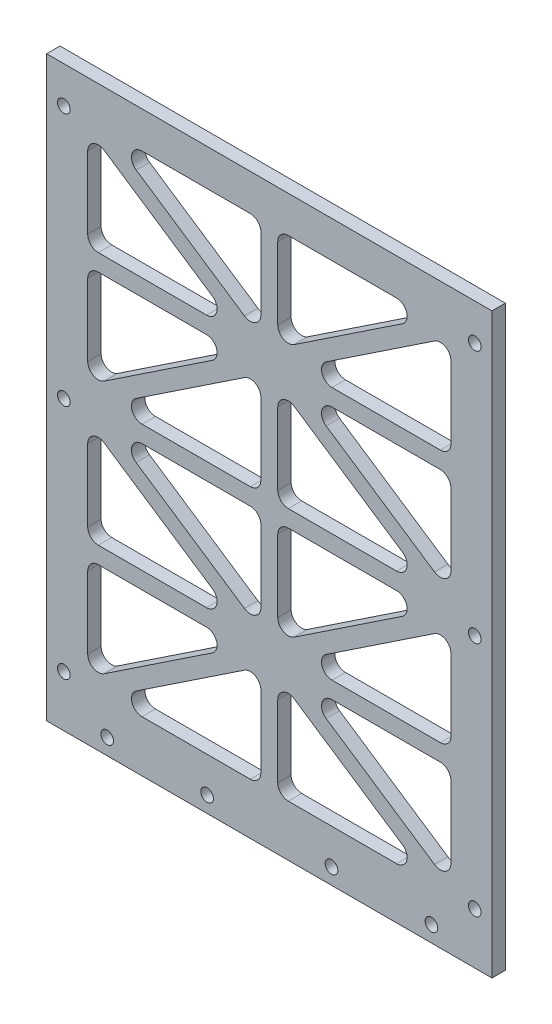
SolidWorks part; units mm, degrees
ref_plane "Front Plane" through (0, 0, 0) normal (0, 0, 1) x (1, 0, 0)
ref_plane "Top Plane" through (0, 0, 0) normal (0, 1, 0) x (1, 0, 0)
ref_plane "Right Plane" through (0, 0, 0) normal (1, 0, 0) x (0, 0, -1)
sketch "Sketch1" plane through (0, 0, 0) normal (0, 0, 1) x (1, 0, 0)
  line L0 (0, -116.2131) -> (0, -56.2131) construction
  line L1 (4, 119.7869) -> (4, 71.261)
  line L2 (76.7889, 119.7869) -> (4, 71.261)
  line L3 (0, -116.2131) -> (90, -116.2131) construction
  line L4 (90, -116.2131) -> (90, -56.2131) construction
  line L5 (0, 137.103) -> (0, -136.5077)
  line L6 (0, -136.5077) -> (105.4703, -136.5077)
  line L7 (0, -56.2131) -> (90, -116.2131) construction
  line L8 (0, -56.2131) -> (90, -56.2131) construction
  line L9 (90, -56.2131) -> (90, 3.7869) construction
  line L10 (90, 3.7869) -> (0, -56.2131) construction
  line L11 (0, -56.2131) -> (0, 3.7869) construction
  line L12 (0, 3.7869) -> (90, 3.7869) construction
  line L13 (90, 3.7869) -> (0, 63.7869) construction
  line L14 (0, 63.7869) -> (0, 3.7869) construction
  line L15 (0, 63.7869) -> (90, 63.7869) construction
  line L16 (90, 63.7869) -> (90, 3.7869) construction
  line L17 (90, 63.7869) -> (90, 123.7869) construction
  line L18 (90, 123.7869) -> (0, 63.7869) construction
  line L19 (0, 123.7869) -> (90, 123.7869) construction
  line L20 (0, 123.7869) -> (0, 63.7869) construction
  line L21 (4, 119.7869) -> (76.7889, 119.7869)
  line L22 (86, 116.3128) -> (13.2111, 67.7869)
  line L23 (13.2111, 67.7869) -> (86, 67.7869)
  line L24 (86, 67.7869) -> (86, 116.3128)
  line L25 (13.2111, 59.7869) -> (86, 59.7869)
  line L26 (86, 59.7869) -> (86, 11.261)
  line L27 (86, 11.261) -> (13.2111, 59.7869)
  line L28 (76.7889, 7.7869) -> (4, 56.3128)
  line L29 (4, 56.3128) -> (4, 7.7869)
  line L30 (4, 7.7869) -> (76.7889, 7.7869)
  line L31 (4, -0.2131) -> (76.7889, -0.2131)
  line L32 (76.7889, -0.2131) -> (4, -48.739)
  line L33 (4, -48.739) -> (4, -0.2131)
  line L34 (86, -3.6872) -> (13.2111, -52.2131)
  line L35 (13.2111, -52.2131) -> (86, -52.2131)
  line L36 (86, -52.2131) -> (86, -3.6872)
  line L37 (13.2111, -60.2131) -> (86, -60.2131)
  line L38 (86, -108.739) -> (86, -60.2131)
  line L39 (13.2111, -60.2131) -> (86, -108.739)
  line L40 (4, -112.2131) -> (4, -63.6872)
  line L41 (4, -63.6872) -> (76.7889, -112.2131)
  line L42 (4, -112.2131) -> (76.7889, -112.2131)
  line L43 (105.4703, -136.5077) -> (105.4703, 137.103)
  line L44 (105.4703, 137.103) -> (0, 137.103)
  circle A0 centre (29.4553, -128.9373) radius 3
  circle A1 centre (76.7889, -128.9373) radius 3
  circle A2 centre (97.307, 119.7869) radius 3
  circle A3 centre (97.307, -0.2131) radius 3
  circle A4 centre (97.307, -112.2131) radius 3
  point P0 (0, 0)
  point P50 (106.125, 119.7869)
  point P51 (77.7234, -123.799)
  point P52 (28.9021, -123.799)
  point P53 (97.307, 119.7869)
  point P54 (97.307, -0.2131)
  point P55 (97.307, -112.2131)
  point P56 (76.7889, -128.9373)
  point P57 (29.4553, -128.9373)
  dimension "D12" = 6
  dimension "D2" = 240
  dimension "D11" = 90
  dimension "D3" = 4
  dimension "D4" = 4
  dimension "D5" = 4
  dimension "D6" = 4
  dimension "D7" = 4
  dimension "D8" = 4
  dimension "D9" = 4
  dimension "D10" = 4
extrude "Boss-Extrude2" add sketch "Sketch1" along normal blind 6.35
fillet "Cutout_Fillets" radius 5 24 edges at (4, 71.261, 3.175) (76.7889, 119.7869, 3.175) (4, 119.7869, 3.175) (13.2111, 67.7869, 3.175) (86, 67.7869, 3.175) (86, 116.3128, 3.175) (86, 11.261, 3.175) (86, 59.7869, 3.175) (13.2111, 59.7869, 3.175) (4, 7.7869, 3.175) (4, 56.3128, 3.175) (76.7889, 7.7869, 3.175) (76.7889, -0.2131, 3.175) (4, -0.2131, 3.175) (4, -48.739, 3.175) (86, -52.2131, 3.175) (86, -3.6872, 3.175) (13.2111, -52.2131, 3.175) (13.2111, -60.2131, 3.175) (86, -60.2131, 3.175) (86, -108.739, 3.175) (76.7889, -112.2131, 3.175) (4, -112.2131, 3.175) (4, -63.6872, 3.175)
mirror "Mirror2" about plane through (0, 137.103, 6.35) normal (1, 0, 0) of "Cutout_Fillets", "Boss-Extrude2"
